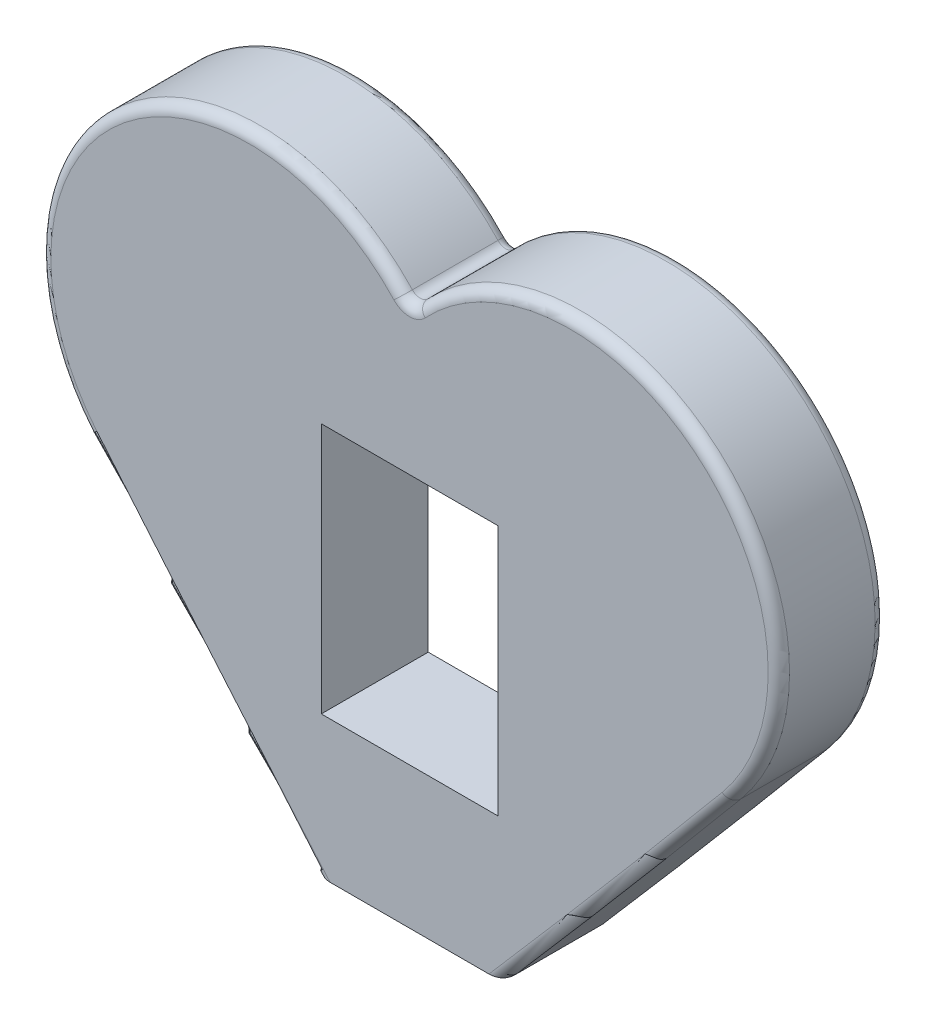
SolidWorks part; units mm, degrees
material "Buk"
ref_plane "Płaszczyzna przednia" through (0, 0, 0) normal (0, 0, 1) x (1, 0, 0)
ref_plane "Płaszczyzna górna" through (0, 0, 0) normal (0, 1, 0) x (1, 0, 0)
ref_plane "Płaszczyzna prawa" through (0, 0, 0) normal (1, 0, 0) x (0, 0, -1)
sketch "Szkic1" plane through (0, 0, 0) normal (0, 0, 1) x (1, 0, 0)
  line L0 (0, -49.9475) -> (0, 50.0525) construction
  line L1 (-17.5, -49.9475) -> (17.5, -49.9475)
  arc A0 (17.5, -49.9475) -> (60, 0) centre (-2520.6973, 2152.8434) ccw
  arc A1 (60, 0) -> (0, 50.0525) centre (30, 25.0263) ccw
  arc A2 (-17.5, -49.9475) -> (-60, 0) centre (2520.6973, 2152.8434) cw
  arc A3 (-60, 0) -> (0, 50.0525) centre (-30, 25.0263) cw
  point P10 (0, 0.0525)
  point P13 (0, 0.0525)
  dimension "D2" = 35
  dimension "D6" = 60
  dimension "D1" = 100
  dimension "D4" = 60
extrude "Dodanie-wyciągnięcie1" add sketch "Szkic1" against normal blind 20
fillet "Zaokrąglenie1" radius 2 11 edges at (-17.5, -49.9475, -10) (-38.8718, -25.0774, -20) (-38.8718, -25.0774, 0) (-55.0263, 55.0263, -20) (-55.0263, 55.0263, 0) (38.8718, -25.0774, -20) (17.5, -49.9475, -10) (38.8718, -25.0774, 0) (0, 50.0525, -10) (55.0263, 55.0263, -20) (55.0263, 55.0263, 0)
sketch "Szkic4" plane through (0, 0, 0) normal (0, 0, 1) x (1, 0, 0)
  line L1 (-16.5, -23.5) -> (16.5, -23.5)
  line L2 (-16.5, -23.5) -> (-16.5, 23.5)
  line L3 (-16.5, 23.5) -> (16.5, 23.5)
  line L4 (16.5, -23.5) -> (16.5, 23.5)
  line L5 (-16.5, -23.5) -> (16.5, 23.5) construction
  line L6 (-16.5, 23.5) -> (16.5, -23.5) construction
  point P0 (0, 0)
  dimension "D1" = 33
  dimension "D2" = 47
extrude "Wytnij-wyciągnięcie1" cut sketch "Szkic4" against normal through all both and the other way through all
